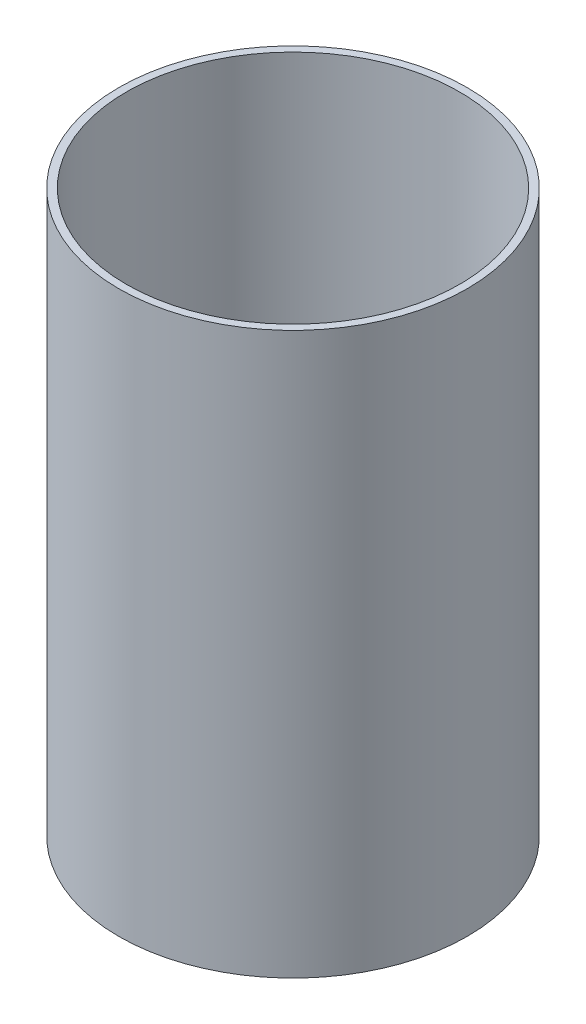
SolidWorks part; units mm, degrees
ref_plane "Plan de face" through (0, 0, 0) normal (0, 0, 1) x (1, 0, 0)
ref_plane "Plan de dessus" through (0, 0, 0) normal (0, 1, 0) x (1, 0, 0)
ref_plane "Plan de droite" through (0, 0, 0) normal (1, 0, 0) x (0, 0, -1)
sketch "Esquisse1" plane through (0, 0, 0) normal (0, 0, 1) x (1, 0, 0)
  line L0 (0, 86.3245) -> (0, -103.3413) construction
  line L1 (80.75, 165.8761) -> (77.25, 165.8761)
  line L2 (80.75, 165.8761) -> (80.75, -94.1239)
  line L3 (77.25, 165.8761) -> (77.25, -94.1239)
  line L4 (77.25, -94.1239) -> (80.75, -94.1239)
  dimension "D1" = 3.5
  dimension "D2" = 77.25
  dimension "D3" = 260
revolve "Révolution1" add sketch "Esquisse1" angle 360 about L0
